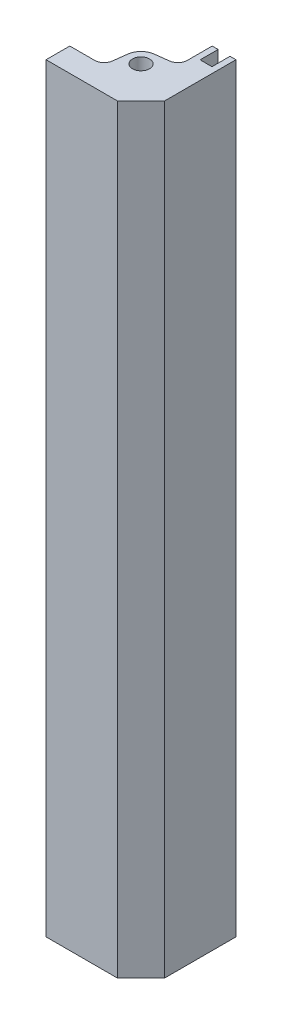
SolidWorks part; units mm, degrees
ref_plane "Front Plane" through (0, 0, 0) normal (0, 0, 1) x (1, 0, 0)
ref_plane "Top Plane" through (0, 0, 0) normal (0, 1, 0) x (1, 0, 0)
ref_plane "Right Plane" through (0, 0, 0) normal (1, 0, 0) x (0, 0, -1)
sketch "Sketch1" plane through (0, 0, 0) normal (0, 1, 0) x (1, 0, 0)
  line L0 (0, 0) -> (25.4, 0)
  line L1 (25.4, 0) -> (25.4, 25.4)
  line L2 (25.4, 25.4) -> (19.05, 25.4)
  line L3 (19.05, 25.4) -> (19.05, 6.35)
  line L4 (19.05, 6.35) -> (0, 6.35)
  line L5 (0, 6.35) -> (0, 0)
  dimension "D1" = 25.4
  dimension "D2" = 6.35
extrude "Boss-Extrude1" add sketch "Sketch1" along normal blind 203.2
sketch "Sketch2" plane through (0, 203.2, 0) normal (0, 1, 0) x (1, 0, 0)
  line L0 (19.05, 25.4) -> (19.05, 6.35) construction
  line L1 (19.05, 6.35) -> (0, 6.35) construction
  line L2 (19.05, 16.51) -> (19.05, 6.35)
  line L3 (19.05, 6.35) -> (8.89, 6.35)
  line L4 (8.89, 6.35) -> (9.6295, 12.244)
  line L5 (19.05, 16.51) -> (13.156, 15.7705)
  line L6 (13.6618, 11.7382) -> (19.05, 6.35) construction
  arc A0 (13.156, 15.7705) -> (9.6295, 12.244) centre (13.6618, 11.7382) ccw
  circle A1 centre (13.6618, 11.7382) radius 2.286
  dimension "D4" = 4.572
  dimension "D5" = 1.778
  dimension "D1" = 45
  dimension "D2" = 10.16
  dimension "D3" = 10.16
  dimension "D6" = 7.62
extrude "Boss-Extrude2" add sketch "Sketch2" against normal blind 6.35
ref_plane "Plane1" through (0, 101.6, 0) normal (0, 1, 0) x (1, 0, 0)
fillet "Fillet1" radius 2.54 2 edges at (19.05, 200.025, -16.51) (8.89, 200.025, -6.35)
mirror "Mirror1" about plane through (0, 101.6, 0) normal (0, 1, 0) of "Fillet1", "Boss-Extrude2"
sketch "Sketch4" plane through (0, 0, 0) normal (0, -1, 0) x (1, 0, 0)
  line L0 (25.4, -25.4) -> (19.05, -25.4) construction
  line L1 (20.6375, -25.4) -> (23.8125, -25.4)
  line L2 (20.6375, -25.4) -> (20.6375, -20.574)
  line L3 (20.6375, -20.574) -> (23.8125, -20.574)
  line L4 (23.8125, -25.4) -> (23.8125, -20.574)
  point P6 (22.225, -25.4)
  point P7 (22.225, -25.4)
  dimension "D1" = 3.175
  dimension "D2" = 4.826
extrude "Cut-Extrude2" cut sketch "Sketch4" against normal through all
sketch "Sketch5" plane through (19.05, 0, 0) normal (-1, 0, 0) x (0, 0, 1)
  line L0 (-25.4, 203.2) -> (-25.4, 0) construction
  line L1 (-25.4, 182.372) -> (-6.35, 182.372) construction
  line L2 (-25.4, 182.372) -> (-25.4, 185.42) construction
  line L3 (-25.4, 185.42) -> (-6.35, 185.42) construction
  line L4 (-6.35, 182.372) -> (-6.35, 185.42) construction
  line L5 (-6.35, 196.85) -> (-6.35, 6.35) construction
  line L6 (-25.4, 179.324) -> (-25.4, 182.372)
  line L7 (-25.4, 176.276) -> (-25.4, 179.324) construction
  line L8 (-25.4, 176.276) -> (-6.35, 176.276) construction
  line L9 (-6.35, 176.276) -> (-6.35, 179.324) construction
  line L10 (-25.4, 179.324) -> (-6.35, 179.324) construction
  line L11 (-25.4, 170.18) -> (-25.4, 173.228) construction
  line L12 (-25.4, 170.18) -> (-6.35, 170.18) construction
  line L13 (-6.35, 170.18) -> (-6.35, 173.228) construction
  line L14 (-25.4, 173.228) -> (-6.35, 173.228) construction
  line L15 (-25.4, 164.084) -> (-25.4, 167.132) construction
  line L16 (-25.4, 164.084) -> (-6.35, 164.084) construction
  line L17 (-6.35, 164.084) -> (-6.35, 167.132) construction
  line L18 (-25.4, 167.132) -> (-6.35, 167.132) construction
  line L19 (-25.4, 157.988) -> (-25.4, 161.036) construction
  line L20 (-25.4, 157.988) -> (-6.35, 157.988) construction
  line L21 (-6.35, 157.988) -> (-6.35, 161.036) construction
  line L22 (-25.4, 161.036) -> (-6.35, 161.036) construction
  line L23 (-25.4, 151.892) -> (-25.4, 154.94) construction
  line L24 (-25.4, 151.892) -> (-6.35, 151.892) construction
  line L25 (-6.35, 151.892) -> (-6.35, 154.94) construction
  line L26 (-25.4, 154.94) -> (-6.35, 154.94) construction
  line L27 (-25.4, 145.796) -> (-25.4, 148.844) construction
  line L28 (-25.4, 145.796) -> (-6.35, 145.796) construction
  line L29 (-6.35, 145.796) -> (-6.35, 148.844) construction
  line L30 (-25.4, 148.844) -> (-6.35, 148.844) construction
  line L31 (-25.4, 139.7) -> (-25.4, 142.748) construction
  line L32 (-25.4, 139.7) -> (-6.35, 139.7) construction
  line L33 (-6.35, 139.7) -> (-6.35, 142.748) construction
  line L34 (-25.4, 142.748) -> (-6.35, 142.748) construction
  line L35 (-25.4, 133.604) -> (-25.4, 136.652) construction
  line L36 (-25.4, 133.604) -> (-6.35, 133.604) construction
  line L37 (-6.35, 133.604) -> (-6.35, 136.652) construction
  line L38 (-25.4, 136.652) -> (-6.35, 136.652) construction
  line L39 (-25.4, 127.508) -> (-25.4, 130.556) construction
  line L40 (-25.4, 127.508) -> (-6.35, 127.508) construction
  line L41 (-6.35, 127.508) -> (-6.35, 130.556) construction
  line L42 (-25.4, 130.556) -> (-6.35, 130.556) construction
  line L43 (-25.4, 121.412) -> (-25.4, 124.46) construction
  line L44 (-25.4, 121.412) -> (-6.35, 121.412) construction
  line L45 (-6.35, 121.412) -> (-6.35, 124.46) construction
  line L46 (-25.4, 124.46) -> (-6.35, 124.46) construction
  line L47 (-25.4, 115.316) -> (-25.4, 118.364) construction
  line L48 (-25.4, 115.316) -> (-6.35, 115.316) construction
  line L49 (-6.35, 115.316) -> (-6.35, 118.364) construction
  line L50 (-25.4, 118.364) -> (-6.35, 118.364) construction
  line L51 (-25.4, 109.22) -> (-25.4, 112.268) construction
  line L52 (-25.4, 109.22) -> (-6.35, 109.22) construction
  line L53 (-6.35, 109.22) -> (-6.35, 112.268) construction
  line L54 (-25.4, 112.268) -> (-6.35, 112.268) construction
  line L55 (-25.4, 103.124) -> (-25.4, 106.172) construction
  line L56 (-25.4, 103.124) -> (-6.35, 103.124) construction
  line L57 (-6.35, 103.124) -> (-6.35, 106.172) construction
  line L58 (-25.4, 106.172) -> (-6.35, 106.172) construction
  line L59 (-25.4, 97.028) -> (-25.4, 100.076) construction
  line L60 (-25.4, 97.028) -> (-6.35, 97.028) construction
  line L61 (-6.35, 97.028) -> (-6.35, 100.076) construction
  line L62 (-25.4, 100.076) -> (-6.35, 100.076) construction
  line L63 (-25.4, 90.932) -> (-25.4, 93.98) construction
  line L64 (-25.4, 90.932) -> (-6.35, 90.932) construction
  line L65 (-6.35, 90.932) -> (-6.35, 93.98) construction
  line L66 (-25.4, 93.98) -> (-6.35, 93.98) construction
  line L67 (-25.4, 84.836) -> (-25.4, 87.884) construction
  line L68 (-25.4, 84.836) -> (-6.35, 84.836) construction
  line L69 (-6.35, 84.836) -> (-6.35, 87.884) construction
  line L70 (-25.4, 87.884) -> (-6.35, 87.884) construction
  line L71 (-25.4, 78.74) -> (-25.4, 81.788) construction
  line L72 (-25.4, 78.74) -> (-6.35, 78.74) construction
  line L73 (-6.35, 78.74) -> (-6.35, 81.788) construction
  line L74 (-25.4, 81.788) -> (-6.35, 81.788) construction
  line L75 (-25.4, 72.644) -> (-25.4, 75.692) construction
  line L76 (-25.4, 72.644) -> (-6.35, 72.644) construction
  line L77 (-6.35, 72.644) -> (-6.35, 75.692) construction
  line L78 (-25.4, 75.692) -> (-6.35, 75.692) construction
  line L79 (-25.4, 66.548) -> (-25.4, 69.596) construction
  line L80 (-25.4, 66.548) -> (-6.35, 66.548) construction
  line L81 (-6.35, 66.548) -> (-6.35, 69.596) construction
  line L82 (-25.4, 69.596) -> (-6.35, 69.596) construction
  line L83 (-25.4, 60.452) -> (-25.4, 63.5) construction
  line L84 (-25.4, 60.452) -> (-6.35, 60.452) construction
  line L85 (-6.35, 60.452) -> (-6.35, 63.5) construction
  line L86 (-25.4, 63.5) -> (-6.35, 63.5) construction
  line L87 (-25.4, 54.356) -> (-25.4, 57.404) construction
  line L88 (-25.4, 54.356) -> (-6.35, 54.356) construction
  line L89 (-6.35, 54.356) -> (-6.35, 57.404) construction
  line L90 (-25.4, 57.404) -> (-6.35, 57.404) construction
  line L91 (-25.4, 48.26) -> (-25.4, 51.308) construction
  line L92 (-25.4, 48.26) -> (-6.35, 48.26) construction
  line L93 (-6.35, 48.26) -> (-6.35, 51.308) construction
  line L94 (-25.4, 51.308) -> (-6.35, 51.308) construction
  line L95 (-25.4, 42.164) -> (-25.4, 45.212) construction
  line L96 (-25.4, 42.164) -> (-6.35, 42.164) construction
  line L97 (-6.35, 42.164) -> (-6.35, 45.212) construction
  line L98 (-25.4, 45.212) -> (-6.35, 45.212) construction
  line L99 (-25.4, 36.068) -> (-25.4, 39.116) construction
  line L100 (-25.4, 36.068) -> (-6.35, 36.068) construction
  line L101 (-6.35, 36.068) -> (-6.35, 39.116) construction
  line L102 (-25.4, 39.116) -> (-6.35, 39.116) construction
  line L103 (-25.4, 29.972) -> (-25.4, 33.02) construction
  line L104 (-25.4, 29.972) -> (-6.35, 29.972) construction
  line L105 (-6.35, 29.972) -> (-6.35, 33.02) construction
  line L106 (-25.4, 33.02) -> (-6.35, 33.02) construction
  line L107 (-25.4, 23.876) -> (-25.4, 26.924) construction
  line L108 (-25.4, 23.876) -> (-6.35, 23.876) construction
  line L109 (-6.35, 23.876) -> (-6.35, 26.924) construction
  line L110 (-25.4, 26.924) -> (-6.35, 26.924) construction
  line L111 (-25.4, 17.78) -> (-25.4, 20.828) construction
  line L112 (-25.4, 17.78) -> (-6.35, 17.78) construction
  line L113 (-6.35, 17.78) -> (-6.35, 20.828) construction
  line L114 (-25.4, 20.828) -> (-6.35, 20.828) construction
  line L115 (-25.4, 185.42) -> (-25.4, 17.78) construction
  line L116 (-25.4, 185.42) -> (-6.35, 185.42)
  line L121 (-25.4, 185.42) -> (-25.4, 188.468)
  line L122 (-25.4, 188.468) -> (-6.35, 188.468)
  line L123 (-6.35, 185.42) -> (-6.35, 188.468)
  line L124 (-25.4, 179.324) -> (-6.35, 179.324)
  line L125 (-6.35, 179.324) -> (-6.35, 182.372)
  line L126 (-25.4, 182.372) -> (-6.35, 182.372)
  line L127 (-25.4, 173.228) -> (-25.4, 176.276)
  line L128 (-25.4, 173.228) -> (-6.35, 173.228)
  line L129 (-6.35, 173.228) -> (-6.35, 176.276)
  line L130 (-25.4, 176.276) -> (-6.35, 176.276)
  line L131 (-25.4, 167.132) -> (-25.4, 170.18)
  line L132 (-25.4, 167.132) -> (-6.35, 167.132)
  line L133 (-6.35, 167.132) -> (-6.35, 170.18)
  line L134 (-25.4, 170.18) -> (-6.35, 170.18)
  line L135 (-25.4, 161.036) -> (-25.4, 164.084)
  line L136 (-25.4, 161.036) -> (-6.35, 161.036)
  line L137 (-6.35, 161.036) -> (-6.35, 164.084)
  line L138 (-25.4, 164.084) -> (-6.35, 164.084)
  line L139 (-25.4, 154.94) -> (-25.4, 157.988)
  line L140 (-25.4, 154.94) -> (-6.35, 154.94)
  line L141 (-6.35, 154.94) -> (-6.35, 157.988)
  line L142 (-25.4, 157.988) -> (-6.35, 157.988)
  line L143 (-25.4, 148.844) -> (-25.4, 151.892)
  line L144 (-25.4, 148.844) -> (-6.35, 148.844)
  line L145 (-6.35, 148.844) -> (-6.35, 151.892)
  line L146 (-25.4, 151.892) -> (-6.35, 151.892)
  line L147 (-25.4, 142.748) -> (-25.4, 145.796)
  line L148 (-25.4, 142.748) -> (-6.35, 142.748)
  line L149 (-6.35, 142.748) -> (-6.35, 145.796)
  line L150 (-25.4, 145.796) -> (-6.35, 145.796)
  line L151 (-25.4, 136.652) -> (-25.4, 139.7)
  line L152 (-25.4, 136.652) -> (-6.35, 136.652)
  line L153 (-6.35, 136.652) -> (-6.35, 139.7)
  line L154 (-25.4, 139.7) -> (-6.35, 139.7)
  line L155 (-25.4, 130.556) -> (-25.4, 133.604)
  line L156 (-25.4, 130.556) -> (-6.35, 130.556)
  line L157 (-6.35, 130.556) -> (-6.35, 133.604)
  line L158 (-25.4, 133.604) -> (-6.35, 133.604)
  line L159 (-25.4, 124.46) -> (-25.4, 127.508)
  line L160 (-25.4, 124.46) -> (-6.35, 124.46)
  line L161 (-6.35, 124.46) -> (-6.35, 127.508)
  line L162 (-25.4, 127.508) -> (-6.35, 127.508)
  line L163 (-25.4, 118.364) -> (-25.4, 121.412)
  line L164 (-25.4, 118.364) -> (-6.35, 118.364)
  line L165 (-6.35, 118.364) -> (-6.35, 121.412)
  line L166 (-25.4, 121.412) -> (-6.35, 121.412)
  line L167 (-25.4, 112.268) -> (-25.4, 115.316)
  line L168 (-25.4, 112.268) -> (-6.35, 112.268)
  line L169 (-6.35, 112.268) -> (-6.35, 115.316)
  line L170 (-25.4, 115.316) -> (-6.35, 115.316)
  line L171 (-25.4, 106.172) -> (-25.4, 109.22)
  line L172 (-25.4, 106.172) -> (-6.35, 106.172)
  line L173 (-6.35, 106.172) -> (-6.35, 109.22)
  line L174 (-25.4, 109.22) -> (-6.35, 109.22)
  line L175 (-25.4, 100.076) -> (-25.4, 103.124)
  line L176 (-25.4, 100.076) -> (-6.35, 100.076)
  line L177 (-6.35, 100.076) -> (-6.35, 103.124)
  line L178 (-25.4, 103.124) -> (-6.35, 103.124)
  line L179 (-25.4, 93.98) -> (-25.4, 97.028)
  line L180 (-25.4, 93.98) -> (-6.35, 93.98)
  line L181 (-6.35, 93.98) -> (-6.35, 97.028)
  line L182 (-25.4, 97.028) -> (-6.35, 97.028)
  line L183 (-25.4, 87.884) -> (-25.4, 90.932)
  line L184 (-25.4, 87.884) -> (-6.35, 87.884)
  line L185 (-6.35, 87.884) -> (-6.35, 90.932)
  line L186 (-25.4, 90.932) -> (-6.35, 90.932)
  line L187 (-25.4, 81.788) -> (-25.4, 84.836)
  line L188 (-25.4, 81.788) -> (-6.35, 81.788)
  line L189 (-6.35, 81.788) -> (-6.35, 84.836)
  line L190 (-25.4, 84.836) -> (-6.35, 84.836)
  line L191 (-25.4, 75.692) -> (-25.4, 78.74)
  line L192 (-25.4, 75.692) -> (-6.35, 75.692)
  line L193 (-6.35, 75.692) -> (-6.35, 78.74)
  line L194 (-25.4, 78.74) -> (-6.35, 78.74)
  line L195 (-25.4, 69.596) -> (-25.4, 72.644)
  line L196 (-25.4, 69.596) -> (-6.35, 69.596)
  line L197 (-6.35, 69.596) -> (-6.35, 72.644)
  line L198 (-25.4, 72.644) -> (-6.35, 72.644)
  line L199 (-25.4, 63.5) -> (-25.4, 66.548)
  line L200 (-25.4, 63.5) -> (-6.35, 63.5)
  line L201 (-6.35, 63.5) -> (-6.35, 66.548)
  line L202 (-25.4, 66.548) -> (-6.35, 66.548)
  line L203 (-25.4, 57.404) -> (-25.4, 60.452)
  line L204 (-25.4, 57.404) -> (-6.35, 57.404)
  line L205 (-6.35, 57.404) -> (-6.35, 60.452)
  line L206 (-25.4, 60.452) -> (-6.35, 60.452)
  line L207 (-25.4, 51.308) -> (-25.4, 54.356)
  line L208 (-25.4, 51.308) -> (-6.35, 51.308)
  line L209 (-6.35, 51.308) -> (-6.35, 54.356)
  line L210 (-25.4, 54.356) -> (-6.35, 54.356)
  line L211 (-25.4, 45.212) -> (-25.4, 48.26)
  line L212 (-25.4, 45.212) -> (-6.35, 45.212)
  line L213 (-6.35, 45.212) -> (-6.35, 48.26)
  line L214 (-25.4, 48.26) -> (-6.35, 48.26)
  line L215 (-25.4, 39.116) -> (-25.4, 42.164)
  line L216 (-25.4, 39.116) -> (-6.35, 39.116)
  line L217 (-6.35, 39.116) -> (-6.35, 42.164)
  line L218 (-25.4, 42.164) -> (-6.35, 42.164)
  line L219 (-25.4, 33.02) -> (-25.4, 36.068)
  line L220 (-25.4, 33.02) -> (-6.35, 33.02)
  line L221 (-6.35, 33.02) -> (-6.35, 36.068)
  line L222 (-25.4, 36.068) -> (-6.35, 36.068)
  line L223 (-25.4, 26.924) -> (-25.4, 29.972)
  line L224 (-25.4, 26.924) -> (-6.35, 26.924)
  line L225 (-6.35, 26.924) -> (-6.35, 29.972)
  line L226 (-25.4, 29.972) -> (-6.35, 29.972)
  line L227 (-25.4, 20.828) -> (-25.4, 23.876)
  line L228 (-25.4, 20.828) -> (-6.35, 20.828)
  line L229 (-6.35, 20.828) -> (-6.35, 23.876)
  line L230 (-25.4, 23.876) -> (-6.35, 23.876)
  line L231 (-25.4, 14.732) -> (-25.4, 17.78)
  line L232 (-25.4, 14.732) -> (-6.35, 14.732)
  line L233 (-6.35, 14.732) -> (-6.35, 17.78)
  line L234 (-25.4, 17.78) -> (-6.35, 17.78)
  point P9 (-6.35, 101.6)
  point P10 (-25.4, 101.6)
  dimension "D1" = 3.048
  dimension "D2" = 3.048
  dimension "D3" = 28
  dimension "D4" = 3.048
  dimension "D5" = 29
extrude "Boss-Extrude3" add sketch "Sketch5" along normal up to surface (19.05 mm away) up to face at (0, 101.6, -3.175)
chamfer "Chamfer1" distance 6.35 angle 45 1 edges at (25.4, 101.6, 0)
sketch "Sketch6" plane through (0, 188.468, 0) normal (0, 1, 0) x (1, 0, 0)
  line L0 (0, 6.35) -> (19.05, 6.35) construction
  line L1 (0, 25.4) -> (14.2875, 25.4)
  line L2 (0, 25.4) -> (0, 11.1125)
  line L3 (0, 11.1125) -> (14.2875, 11.1125)
  line L4 (14.2875, 25.4) -> (14.2875, 11.1125)
  dimension "D1" = 4.7625
extrude "Cut-Extrude3" cut sketch "Sketch6" against normal up to surface (173.736 mm away) up to face at (9.525, 14.732, -15.875)
